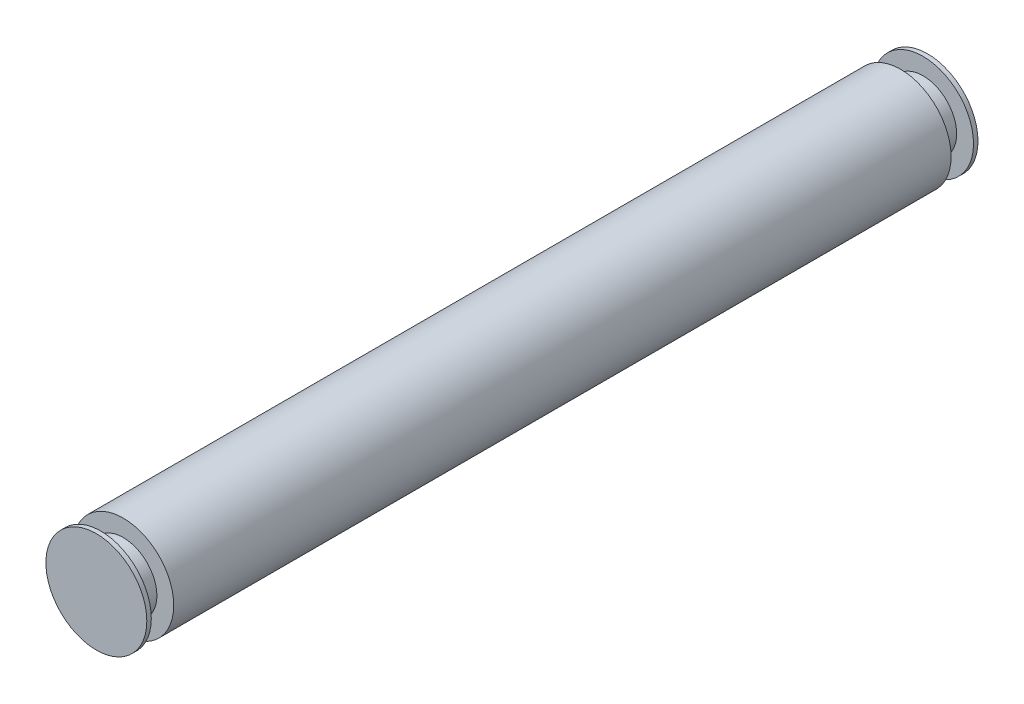
SolidWorks part; units mm, degrees
ref_plane "Front Plane" through (0, 0, 0) normal (0, 0, 1) x (1, 0, 0)
ref_plane "Top Plane" through (0, 0, 0) normal (0, 1, 0) x (1, 0, 0)
ref_plane "Right Plane" through (0, 0, 0) normal (1, 0, 0) x (0, 0, -1)
sketch "Sketch1" plane through (0, 0, 0) normal (0, 0, 1) x (1, 0, 0)
  circle A0 centre (0, 0) radius 22.5
  dimension "D1" = 45
extrude "Boss-Extrude1" add sketch "Sketch1" along normal mid plane 346.67
sketch "Sketch2" plane through (0, 0, 173.335) normal (0, 0, 1) x (1, 0, 0)
  circle A2 centre (0, 0) radius 15
  circle A3 centre (0, 0) radius 15
  dimension "D1" = 7.5
extrude "Boss-Extrude2" add sketch "Sketch2" along normal blind 10
sketch "Sketch3" plane through (0, 0, 183.335) normal (0, 0, 1) x (1, 0, 0)
  circle A2 centre (0, 0) radius 22.5
  circle A3 centre (0, 0) radius 22.5
  dimension "D1" = 7.5
extrude "Boss-Extrude3" add sketch "Sketch3" along normal blind 2
mirror "Mirror1" about plane through (0, 0, 0) normal (0, 0, 1) of "Boss-Extrude2", "Boss-Extrude3"
